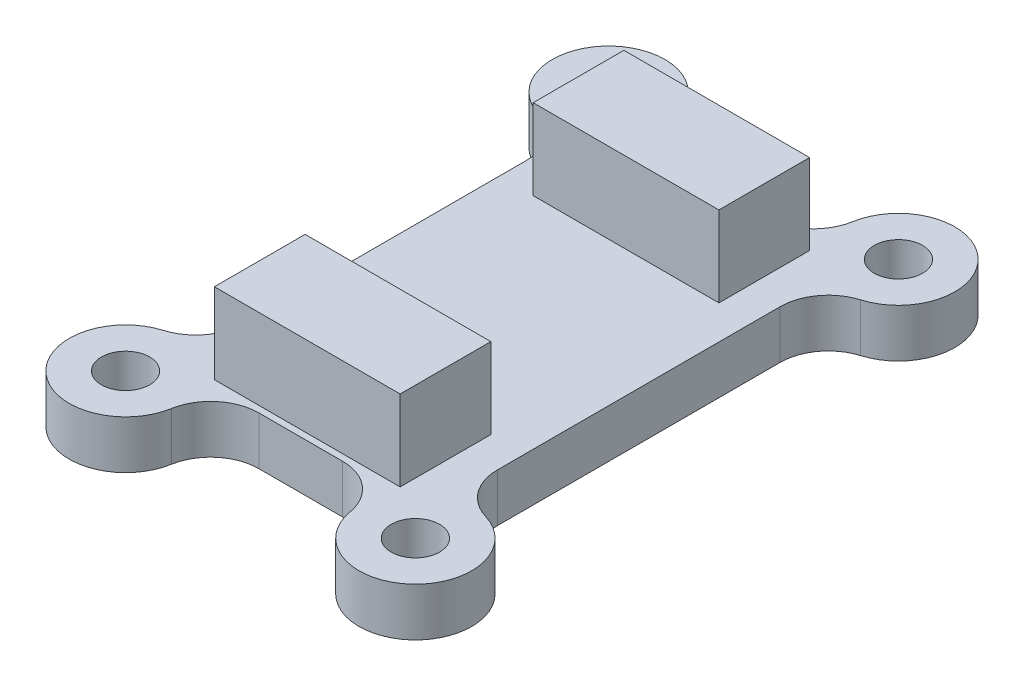
SolidWorks part; units mm, degrees
ref_plane "Front Plane" through (0, 0, 0) normal (0, 0, 1) x (1, 0, 0)
ref_plane "Top Plane" through (0, 0, 0) normal (0, 1, 0) x (1, 0, 0)
ref_plane "Right Plane" through (0, 0, 0) normal (1, 0, 0) x (0, 0, -1)
sketch "Sketch1" plane through (0, 0, 0) normal (0, 1, 0) x (1, 0, 0)
  line L1 (-9, 15) -> (9, 15) construction
  line L2 (-9, 15) -> (-9, -15) construction
  line L3 (-9, -15) -> (9, -15) construction
  line L4 (9, 15) -> (9, -15) construction
  line L5 (-9, 15) -> (9, -15) construction
  line L6 (-9, -15) -> (9, 15) construction
  line L7 (-7.8719, 13.1199) -> (7.8719, 13.1199)
  line L8 (-7.8719, 13.1199) -> (-7.8719, -13.1199)
  line L9 (-7.8719, -13.1199) -> (7.8719, -13.1199)
  line L10 (7.8719, 13.1199) -> (7.8719, -13.1199)
  line L11 (-7.8719, 13.1199) -> (7.8719, -13.1199) construction
  line L12 (-7.8719, -13.1199) -> (7.8719, 13.1199) construction
  circle A0 centre (9, 15) radius 1.5
  circle A1 centre (9, -15) radius 1.5
  circle A2 centre (-9, -15) radius 1.5
  circle A3 centre (-9, 15) radius 1.5
  circle A4 centre (9, 15) radius 3.5
  circle A5 centre (9, -15) radius 3.5
  circle A6 centre (-9, -15) radius 3.5
  circle A7 centre (-9, 15) radius 3.5
  point P0 (0, 0)
  point P10 (0, 0)
  point P19 (-7.8719, -13.1199)
  dimension "D3" = 3
  dimension "D4" = 2
  dimension "D1" = 18
  dimension "D2" = 30
extrude "Boss-Extrude1" add sketch "Sketch1" along normal blind 3 contours A7 L8 A6 L9 A5 L10 A4 L7 | L9 A5 L10 A1 | L10 A5 L9 | L9 A6 L8 | L8 A6 L9 A2 | L7 A4 L10 | L10 A4 L7 A0 | L8 A7 L7 | L7 A7 L8 A3
fillet "Fillet1" radius 3 8 edges at (-7.8719, 1.5, -11.6868) (7.8719, 1.5, -11.6868) (6.0478, 1.5, -13.1199) (-6.0478, 1.5, -13.1199) (-7.8719, 1.5, 11.6868) (-6.0478, 1.5, 13.1199) (6.0478, 1.5, 13.1199) (7.8719, 1.5, 11.6868)
sketch "Sketch2" plane through (0, 3, 0) normal (0, 1, 0) x (1, 0, 0)
  line L0 (0, 0) -> (0, -7.0819) construction
  line L1 (-5.7674, 12.7152) -> (5.7674, 12.7152)
  line L2 (-5.7674, 12.7152) -> (-5.7674, 7.0819)
  line L3 (-5.7674, 7.0819) -> (5.7674, 7.0819)
  line L4 (5.7674, 12.7152) -> (5.7674, 7.0819)
  line L5 (-5.7674, -7.0819) -> (5.7674, -7.0819)
  line L6 (-5.7674, -7.0819) -> (-5.7674, -12.7152)
  line L7 (-5.7674, -12.7152) -> (5.7674, -12.7152)
  line L8 (5.7674, -7.0819) -> (5.7674, -12.7152)
  line L9 (0, 0) -> (0, 7.0819) construction
  point P8 (0, 7.0819)
  point P9 (0, -7.0819)
extrude "Boss-Extrude2" add sketch "Sketch2" along normal blind 5
